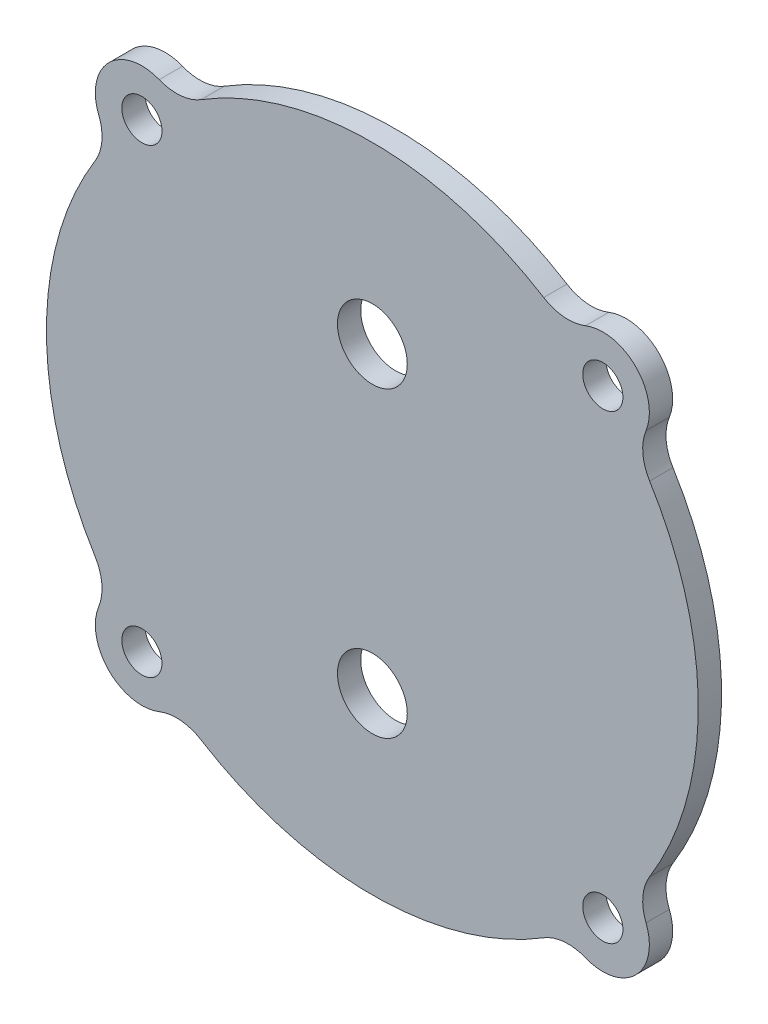
SolidWorks part; units mm, degrees
material "Acrylic (Medium-high impact)"
ref_plane "Front Plane" through (0, 0, 0) normal (0, 0, 1) x (1, 0, 0)
ref_plane "Top Plane" through (0, 0, 0) normal (0, 1, 0) x (1, 0, 0)
ref_plane "Right Plane" through (0, 0, 0) normal (1, 0, 0) x (0, 0, -1)
sketch "Sketch1" plane through (0, 0, 0) normal (0, 0, 1) x (1, 0, 0)
  line L0 (-19.799, 19.799) -> (19.799, -19.799) construction
  line L1 (19.799, 19.799) -> (-19.799, -19.799) construction
  line L2 (-28, 0) -> (28, 0) construction
  arc A0 (16.7758, 22.4182) -> (-16.7758, 22.4182) centre (0, 0) ccw
  circle A1 centre (19.799, 19.799) radius 1.725
  circle A2 centre (-19.799, 19.799) radius 1.725
  circle A3 centre (-19.799, -19.799) radius 1.725
  circle A4 centre (19.799, -19.799) radius 1.725
  arc A5 (-16.7758, 22.4182) -> (-22.4182, 16.7758) centre (-19.799, 19.799) ccw
  arc A6 (22.4182, 16.7758) -> (16.7758, 22.4182) centre (19.799, 19.799) ccw
  arc A7 (-22.4182, -16.7758) -> (-16.7758, -22.4182) centre (-19.799, -19.799) ccw
  arc A8 (16.7758, -22.4182) -> (22.4182, -16.7758) centre (19.799, -19.799) ccw
  arc A9 (-22.4182, 16.7758) -> (-22.4182, -16.7758) centre (0, 0) ccw
  arc A10 (22.4182, -16.7758) -> (22.4182, 16.7758) centre (0, 0) ccw
  arc A11 (-16.7758, -22.4182) -> (16.7758, -22.4182) centre (0, 0) ccw
  circle A12 centre (0, 0) radius 28 construction
  circle A13 centre (0, 13) radius 3
  circle A14 centre (0, -13) radius 3
  dimension "D1" = 13
  dimension "D3" = 3.45
  dimension "D4" = 8
  dimension "D5" = 28
  dimension "D6" = 56
  dimension "D7" = 6
  dimension "D2" = 45
extrude "Boss-Extrude1" add sketch "Sketch1" along normal blind 2
fillet "Fillet1" radius 4 8 edges at (16.7758, 22.4182, 1) (22.4182, 16.7758, 1) (22.4182, -16.7758, 1) (16.7758, -22.4182, 1) (-16.7758, -22.4182, 1) (-22.4182, -16.7758, 1) (-22.4182, 16.7758, 1) (-16.7758, 22.4182, 1)
equation "\"D3@Sketch1\"=3.00mm+\"print_free@Parameters@FabricationParameters.sldprt\""
